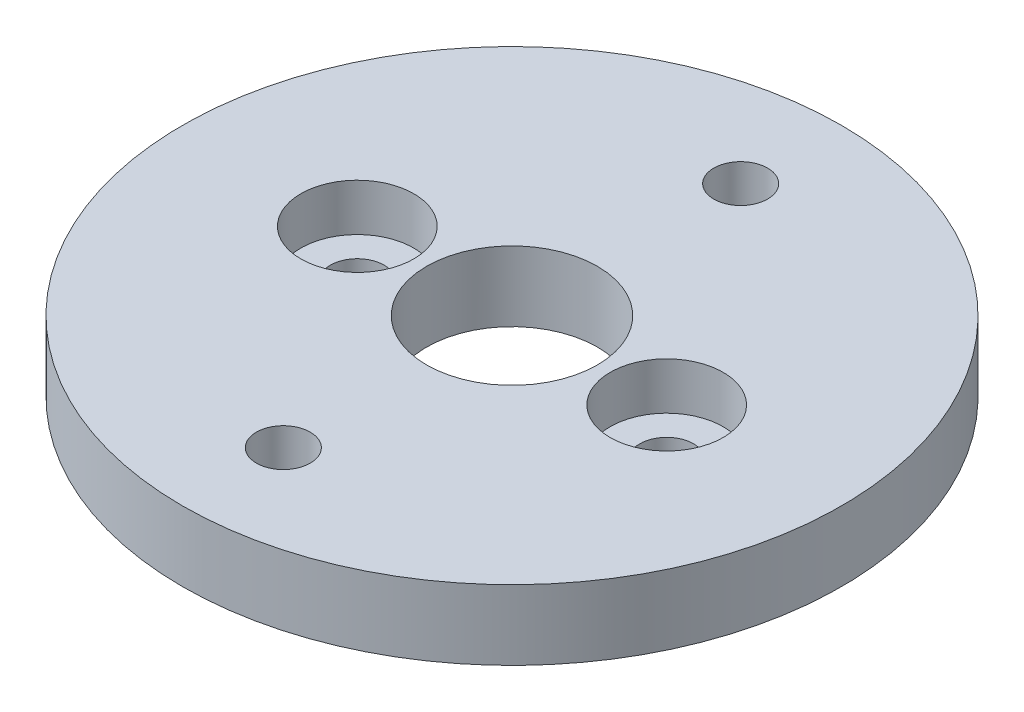
SolidWorks part; units mm, degrees
ref_plane "Front Plane" through (0, 0, 0) normal (0, 0, 1) x (1, 0, 0)
ref_plane "Top Plane" through (0, 0, 0) normal (0, 1, 0) x (1, 0, 0)
ref_plane "Right Plane" through (0, 0, 0) normal (1, 0, 0) x (0, 0, -1)
sketch "Sketch1" plane through (0, 0, 0) normal (0, 1, 0) x (1, 0, 0)
  circle A0 centre (0, 0) radius 12.25
  dimension "D1" = 24.5
extrude "Boss-Extrude1" add sketch "Sketch1" along normal blind 2.6 contours A0
sketch "Sketch2" plane through (0, 0, 0) normal (0, -1, 0) x (1, 0, 0)
  line L0 (0, 8.5) -> (0, -8.5) construction
  line L1 (5.75, 0) -> (-5.75, 0) construction
  circle A0 centre (0, 0) radius 3.175
  circle A1 centre (0, 8.5) radius 1
  circle A2 centre (0, -8.5) radius 1
  circle A3 centre (-5.75, 0) radius 1
  circle A4 centre (5.75, 0) radius 1
  point P4 (0, 0)
  point P8 (0, 0)
  dimension "D2" = 6.35
  dimension "D3" = 2
  dimension "D5" = 2
  dimension "D1" = 17
  dimension "D4" = 11.5
extrude "Cut-Extrude1" cut sketch "Sketch2" against normal up to next
sketch "Sketch3" plane through (0, 2.6, 0) normal (0, 1, 0) x (1, 0, 0)
  circle A0 centre (-5.75, 0) radius 2.1
  circle A1 centre (5.75, 0) radius 2.1
  dimension "D1" = 4.2
extrude "Cut-Extrude2" cut sketch "Sketch3" against normal blind 1.75
